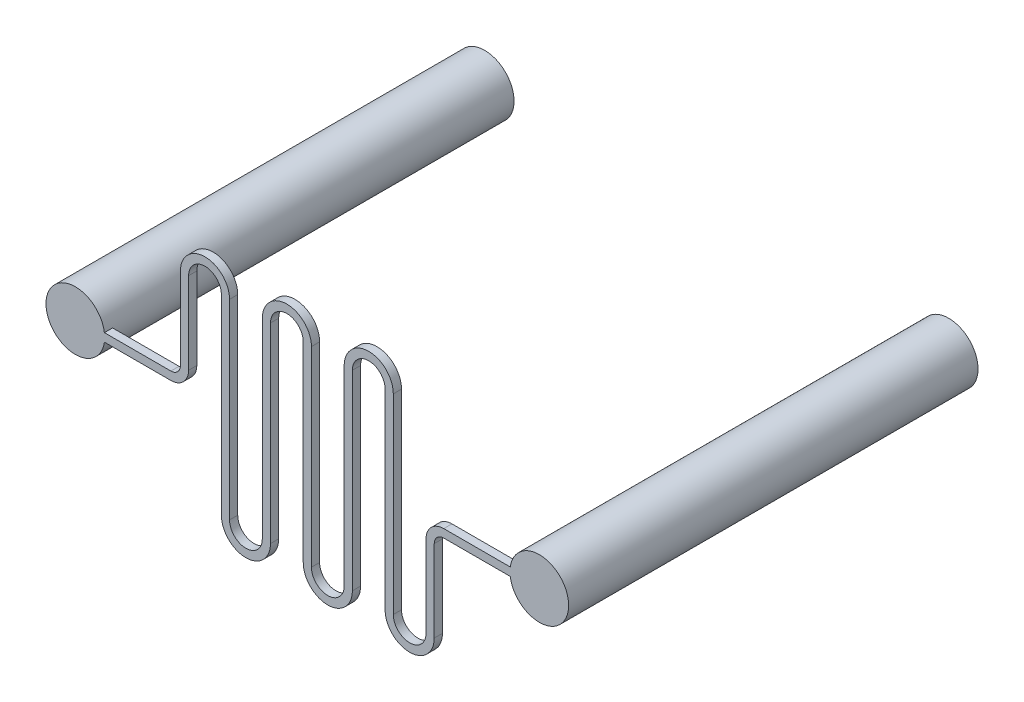
SolidWorks part; units mm, degrees
ref_plane "Front Plane" through (0, 0, 0) normal (0, 0, 1) x (1, 0, 0)
ref_plane "Top Plane" through (0, 0, 0) normal (0, 1, 0) x (1, 0, 0)
ref_plane "Right Plane" through (0, 0, 0) normal (1, 0, 0) x (0, 0, -1)
sketch "Sketch2" plane through (0, 0, 0) normal (0, 0, 1) x (1, 0, 0)
  line L3 (-20.5, -0.3) -> (-13.5, -0.3)
  line L6 (-12.2, 1) -> (-12.2, 7)
  line L9 (-9.8, 7) -> (-9.8, 0)
  line L12 (-9.8, 0) -> (-9.8, -7)
  line L15 (-6.2, -7) -> (-6.2, 0)
  line L18 (-6.2, 0) -> (-6.2, 7)
  line L21 (-3.8, 7) -> (-3.8, 0)
  line L22 (-3.8, 0) -> (-3.8, -7)
  line L23 (-0.2, -7) -> (-0.2, 0)
  line L24 (-0.2, 0) -> (-0.2, 7)
  line L25 (2.2, 7) -> (2.2, 0)
  line L26 (2.2, 0) -> (2.2, -7)
  line L27 (5.8, -7) -> (5.8, -1)
  line L28 (6.5, -0.3) -> (13.5, -0.3)
  line L29 (-20.5, 0.3) -> (-13.5, 0.3)
  line L30 (-12.8, 1) -> (-12.8, 7)
  line L31 (-9.2, 7) -> (-9.2, 0)
  line L32 (-9.2, 0) -> (-9.2, -7)
  line L33 (-6.8, -7) -> (-6.8, 0)
  line L34 (-6.8, 0) -> (-6.8, 7)
  line L35 (-3.2, 7) -> (-3.2, 0)
  line L36 (-3.2, 0) -> (-3.2, -7)
  line L37 (-0.8, -7) -> (-0.8, 0)
  line L38 (-0.8, 0) -> (-0.8, 7)
  line L39 (2.8, 7) -> (2.8, 0)
  line L40 (2.8, 0) -> (2.8, -7)
  line L41 (5.2, -7) -> (5.2, -1)
  line L42 (6.5, 0.3) -> (13.5, 0.3)
  arc A8 (-12.2, 1) -> (-13.5, -0.3) centre (-13.5, 1) cw
  arc A9 (-12.2, 7) -> (-9.8, 7) centre (-11, 7) cw
  arc A10 (-9.8, -7) -> (-6.2, -7) centre (-8, -7) ccw
  arc A11 (-6.2, 7) -> (-3.8, 7) centre (-5, 7) cw
  arc A12 (-3.8, -7) -> (-0.2, -7) centre (-2, -7) ccw
  arc A13 (-0.2, 7) -> (2.2, 7) centre (1, 7) cw
  arc A14 (2.2, -7) -> (5.8, -7) centre (4, -7) ccw
  arc A15 (5.8, -1) -> (6.5, -0.3) centre (6.5, -1) cw
  arc A16 (-12.8, 1) -> (-13.5, 0.3) centre (-13.5, 1) cw
  arc A17 (-12.8, 7) -> (-9.2, 7) centre (-11, 7) cw
  arc A18 (-9.2, -7) -> (-6.8, -7) centre (-8, -7) ccw
  arc A19 (-6.8, 7) -> (-3.2, 7) centre (-5, 7) cw
  arc A20 (-3.2, -7) -> (-0.8, -7) centre (-2, -7) ccw
  arc A21 (-0.8, 7) -> (2.8, 7) centre (1, 7) cw
  arc A22 (2.8, -7) -> (5.2, -7) centre (4, -7) ccw
  arc A23 (5.2, -1) -> (6.5, 0.3) centre (6.5, -1) cw
  arc A24 (-20.5, 0.3) -> (-20.5, -0.3) centre (-20.5, 0) ccw
  arc A25 (13.5, -0.3) -> (13.5, 0.3) centre (13.5, 0) ccw
  point P4 (0, 0)
  point P32 (5.5, 0)
  point P35 (-12.5, 0)
  dimension "D1" = 8
  dimension "D14" = 8
extrude "Boss-Extrude1" add sketch "Sketch2" along normal blind 0.6
ref_plane "Plane1" through (0, 0, 0) normal (0, 1, 0) x (1, 0, 0)
ref_plane "Plane2" through (0, 0, 0) normal (0, 1, 0) x (1, 0, 0)
sketch "Sketch3" plane through (0, 0, 0) normal (0, 1, 0) x (1, 0, 0)
  line L0 (-20.5, -0.6) -> (-22.65, -0.6)
  line L1 (-22.65, -0.6) -> (-22.65, 29.4)
  line L2 (-22.65, 29.4) -> (-20.5, 29.4)
  line L3 (-20.5, 29.4) -> (-20.5, -0.6)
  dimension "D1" = 2.15
  dimension "D2" = 30
revolve "Revolve1" add sketch "Sketch3" angle 360 about L3
sketch "Sketch4" plane through (0, 0, 0) normal (0, 1, 0) x (1, 0, 0)
  line L0 (13.5, -0.6) -> (15.65, -0.6)
  line L1 (15.65, -0.6) -> (15.65, 29.4)
  line L2 (15.65, 29.4) -> (13.5, 29.4)
  line L3 (13.5, 29.4) -> (13.5, -0.6)
  dimension "D1" = 2.15
  dimension "D2" = 30
revolve "Revolve2" add sketch "Sketch4" angle 360 about L3
sketch "Sketch5" plane through (0, 0, -29.4) normal (0, 0, -1) x (-1, 0, 0)
  circle A0 centre (20.5, 0) radius 1.75
  circle A1 centre (-13.5, 0) radius 1.75
  dimension "D1" = 3.5
  dimension "D2" = 3.5
extrude "Cut-Extrude1" cut sketch "Sketch5" against normal blind 29
